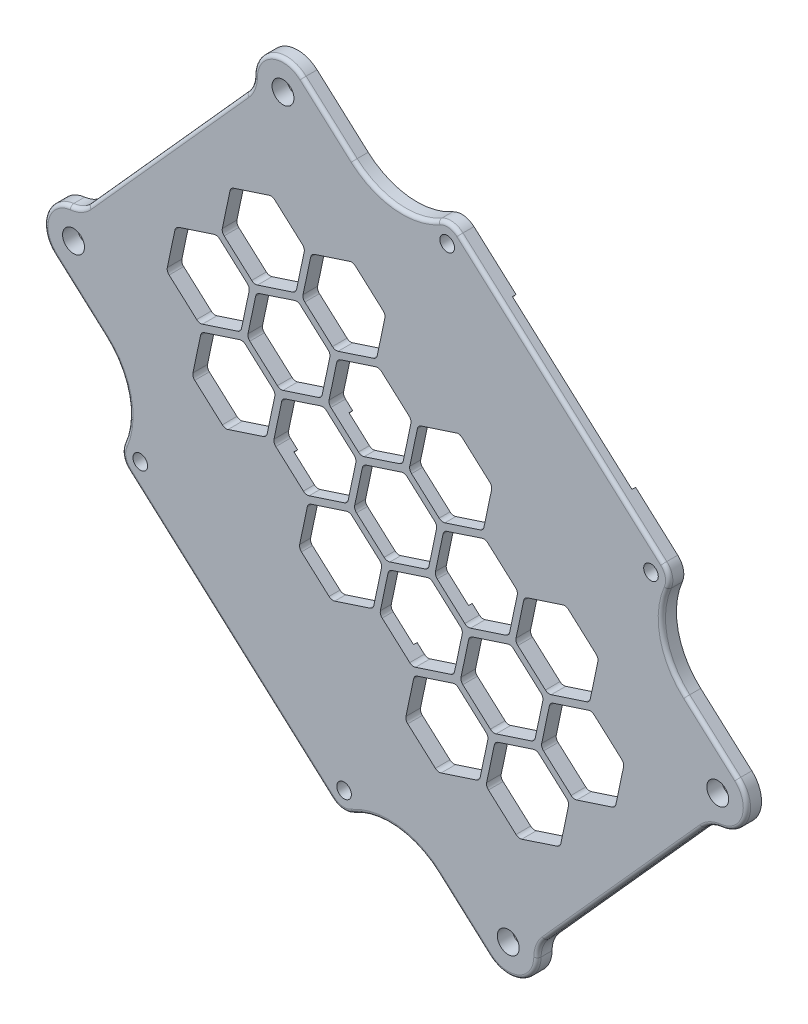
SolidWorks part; units mm, degrees
ref_plane "前视基准面" through (0, 0, 0) normal (0, 0, 1) x (1, 0, 0)
ref_plane "上视基准面" through (0, 0, 0) normal (0, 1, 0) x (1, 0, 0)
ref_plane "右视基准面" through (0, 0, 0) normal (1, 0, 0) x (0, 0, -1)
sketch "草图1" plane through (0, 0, 0) normal (0, 0, 1) x (1, 0, 0)
  line L0 (80, 0.003) -> (139.5685, -53.3973) construction
  line L1 (82.67, 2.9814) -> (142.2386, -50.4188) construction
  line L3 (142.547, -56.0673) -> (113.8443, -88.0854) construction
  line L4 (48.6273, -34.9935) -> (108.1959, -88.3938) construction
  line L5 (79.6916, 5.6514) -> (111.1743, -91.0638) construction
  line L6 (145.217, -53.0889) -> (45.6489, -32.3235) construction
  line L7 (102.4979, -6.7354) -> (130.4207, -31.7668) construction
  line L8 (102.4979, -6.7354) -> (60.4452, -53.6456) construction
  line L9 (130.4207, -31.7668) -> (88.368, -78.677) construction
  line L10 (60.4452, -53.6456) -> (88.368, -78.677) construction
  line L11 (102.4979, -6.7354) -> (88.368, -78.677) construction
  line L12 (130.4207, -31.7668) -> (60.4452, -53.6456) construction
  line L13 (97.7059, -44.7438) -> (73.5507, -23.0898) construction
  line L14 (104.1667, -4.8739) -> (132.0894, -29.9052)
  line L15 (99.4225, -38.2558) -> (108.6518, -27.9604) construction
  line L16 (135.2338, -44.1395) -> (142.2386, -50.4188)
  line L17 (82.67, 2.9814) -> (89.6747, -3.298)
  line L18 (101.1912, -82.1144) -> (108.1959, -88.3938)
  line L19 (58.7765, -55.5071) -> (86.6992, -80.5385)
  line L20 (48.6273, -34.9935) -> (55.6321, -41.2729)
  line L21 (74.9787, -2.6021) -> (53.3402, -26.74)
  line L22 (137.5257, -58.6724) -> (115.8872, -82.8103)
  circle A0 centre (139.5685, -53.3973) radius 1.5 construction
  circle A1 centre (110.8659, -85.4154) radius 1.5 construction
  circle A2 centre (51.2974, -32.0151) radius 1.5 construction
  circle A4 centre (139.5685, -53.3973) radius 1.5
  circle A5 centre (110.8659, -85.4154) radius 1.5
  circle A6 centre (51.2974, -32.0151) radius 1.5
  circle A7 centre (80, 0.003) radius 1.5
  arc A8 (48.3189, -29.3451) -> (48.6273, -34.9935) centre (51.2974, -32.0151) ccw construction
  arc A9 (77.0216, 2.673) -> (82.67, 2.9814) centre (80, 0.003) cw construction
  arc A10 (142.2386, -50.4188) -> (142.547, -56.0673) centre (139.5685, -53.3973) cw construction
  arc A11 (113.8443, -88.0854) -> (108.1959, -88.3938) centre (110.8659, -85.4154) cw construction
  circle A12 centre (102.4979, -6.7354) radius 1
  circle A13 centre (130.4207, -31.7668) radius 1
  circle A14 centre (88.368, -78.677) radius 1
  circle A15 centre (60.4452, -53.6456) radius 1
  circle A16 centre (102.4979, -6.7354) radius 2.5 construction
  circle A17 centre (130.4207, -31.7668) radius 2.5 construction
  circle A18 centre (60.4452, -53.6456) radius 2.5 construction
  circle A19 centre (88.368, -78.677) radius 2.5 construction
  arc A20 (101.2683, -4.5587) -> (89.6747, -3.298) centre (96.3498, 4.1481) cw
  arc A21 (101.2683, -4.5587) -> (104.1667, -4.8739) centre (102.4979, -6.7354) cw
  arc A22 (132.0894, -29.9052) -> (132.7183, -32.7521) centre (130.4207, -31.7668) cw
  arc A23 (132.7183, -32.7521) -> (135.2338, -44.1395) centre (141.9089, -36.6934) ccw
  arc A24 (82.67, 2.9814) -> (77.0216, 2.673) centre (80, 0.003) ccw
  arc A25 (48.3189, -29.3451) -> (48.6273, -34.9935) centre (51.2974, -32.0151) ccw
  arc A26 (113.8443, -88.0854) -> (108.1959, -88.3938) centre (110.8659, -85.4154) cw
  arc A27 (142.2386, -50.4188) -> (142.547, -56.0673) centre (139.5685, -53.3973) cw
  arc A28 (89.5976, -80.8537) -> (101.1912, -82.1144) centre (94.5161, -89.5605) cw
  arc A29 (86.6992, -80.5385) -> (89.5976, -80.8537) centre (88.368, -78.677) ccw
  arc A30 (58.1476, -52.6603) -> (55.6321, -41.2729) centre (48.957, -48.719) ccw
  arc A31 (58.1476, -52.6603) -> (58.7765, -55.5071) centre (60.4452, -53.6456) ccw
  arc A32 (48.3189, -29.3451) -> (50.8296, -28.0425) centre (51.2974, -32.0151) cw
  arc A33 (77.0216, 2.673) -> (76.0001, 0.0355) centre (80, 0.003) ccw
  arc A34 (50.8296, -28.0425) -> (53.3402, -26.74) centre (50.3618, -24.07) ccw
  arc A35 (76.0001, 0.0355) -> (74.9787, -2.6021) centre (72.0003, 0.0679) cw
  arc A36 (113.8443, -88.0854) -> (114.8658, -85.4478) centre (110.8659, -85.4154) ccw
  arc A37 (114.8658, -85.4478) -> (115.8872, -82.8103) centre (118.8656, -85.4803) cw
  arc A38 (140.0363, -57.3698) -> (137.5257, -58.6724) centre (140.5041, -61.3424) ccw
  arc A39 (142.547, -56.0673) -> (140.0363, -57.3698) centre (139.5685, -53.3973) cw
  point P844 (87.6362, -48.7818)
  point P856 (90.2423, -51.1181)
  dimension "D5" = 4
  dimension "D8" = 2
  dimension "D9" = 5
  dimension "D10" = 10
  dimension "D11" = 4
  dimension "D3" = 4
  dimension "D4" = 4
  dimension "D6" = 6
  dimension "D7" = 37.5
extrude "凸台-拉伸1" add sketch "草图1" along normal blind 2
sketch "草图2" plane through (0, 0, 2) normal (0, 0, 1) x (1, 0, 0)
  line L0 (64.1595, -14.671) -> (126.7064, -70.7413) construction
  line L1 (74.9787, -2.6021) -> (53.3402, -26.74) construction
  line L2 (115.8872, -82.8103) -> (137.5257, -58.6724) construction
  line L3 (118.1281, -17.3896) -> (72.7378, -68.0228) construction
  line L4 (132.0894, -29.9052) -> (104.1667, -4.8739) construction
  line L5 (58.7765, -55.5071) -> (86.6992, -80.5385) construction
  line L6 (98.5173, -52.1286) -> (95.864, -44.0231) construction
  line L7 (99.9956, -46.2592) -> (101.0402, -41.2916)
  line L8 (100.7913, -40.5313) -> (97.0115, -37.1429)
  line L9 (96.2286, -36.9783) -> (91.4043, -38.5575)
  line L10 (90.8703, -39.1532) -> (89.8257, -44.1208)
  line L11 (90.0746, -44.8811) -> (93.8544, -48.2695)
  line L12 (94.6373, -48.4341) -> (99.4616, -46.8549)
  line L13 (99.744, -47.7175) -> (94.9197, -49.2967)
  line L14 (94.3857, -49.8924) -> (93.3411, -54.86)
  line L15 (93.59, -55.6203) -> (97.3698, -59.0087)
  line L16 (98.1527, -59.1734) -> (102.977, -57.5942)
  line L17 (103.511, -56.9985) -> (104.5556, -52.0309)
  line L18 (104.3067, -51.2706) -> (100.5269, -47.8822)
  line L19 (105.5662, -46.0632) -> (99.8733, -52.4137) construction
  line L20 (101.1328, -47.2063) -> (104.9126, -50.5947)
  line L21 (105.6955, -50.7593) -> (110.5198, -49.1801)
  line L22 (111.0538, -48.5844) -> (112.0984, -43.6168)
  line L23 (111.8495, -42.8565) -> (108.0697, -39.4681)
  line L24 (107.2868, -39.3035) -> (102.4624, -40.8827)
  line L25 (101.9284, -41.4784) -> (100.8839, -46.446)
  line L26 (105.1351, -44.7463) -> (96.7889, -42.9913) construction
  line L27 (116.7457, -53.135) -> (121.5701, -51.5558)
  line L28 (102.1801, -40.02) -> (107.0044, -38.4408)
  line L29 (107.5384, -37.8451) -> (108.583, -32.8775)
  line L30 (108.3341, -32.1172) -> (104.5543, -28.7288)
  line L31 (103.7714, -28.5642) -> (98.9471, -30.1434)
  line L32 (98.4131, -30.7391) -> (97.3685, -35.7067)
  line L33 (97.6174, -36.467) -> (101.3972, -39.8554)
  line L34 (93.2485, -48.9454) -> (89.4687, -45.5569)
  line L35 (88.6858, -45.3923) -> (83.8615, -46.9715)
  line L36 (83.3275, -47.5672) -> (82.2829, -52.5348)
  line L37 (82.5318, -53.2951) -> (86.3116, -56.6835)
  line L38 (87.0945, -56.8481) -> (91.9188, -55.2689)
  line L39 (92.4528, -54.6733) -> (93.4974, -49.7057)
  line L40 (122.1041, -50.9601) -> (123.1486, -45.9925)
  line L41 (122.8997, -45.2322) -> (119.1199, -41.8438)
  line L42 (118.337, -41.6792) -> (113.5127, -43.2584)
  line L43 (112.9787, -43.8541) -> (111.9341, -48.8217)
  line L44 (112.183, -49.582) -> (115.9628, -52.9704)
  line L45 (115.6984, -60.3212) -> (119.4782, -63.7097)
  line L46 (120.2611, -63.8743) -> (125.0854, -62.2951)
  line L47 (125.6194, -61.6994) -> (126.664, -56.7318)
  line L48 (126.4151, -55.9715) -> (122.6353, -52.5831)
  line L49 (121.8524, -52.4184) -> (117.0281, -53.9977)
  line L50 (116.4941, -54.5933) -> (115.4495, -59.5609)
  line L51 (114.3096, -60.8325) -> (109.4853, -62.4117)
  line L52 (108.9513, -63.0074) -> (107.9067, -67.975)
  line L53 (108.1556, -68.7353) -> (111.9354, -72.1237)
  line L54 (112.7183, -72.2883) -> (117.5427, -70.7091)
  line L55 (118.0767, -70.1134) -> (119.1212, -65.1458)
  line L56 (118.8723, -64.3855) -> (115.0925, -60.9971)
  line L57 (114.5613, -59.3742) -> (115.6058, -54.4066)
  line L58 (115.3569, -53.6463) -> (111.5771, -50.2578)
  line L59 (110.7943, -50.0932) -> (105.9699, -51.6724)
  line L60 (105.4359, -52.2681) -> (104.3914, -57.2357)
  line L61 (104.6402, -57.996) -> (108.42, -61.3844)
  line L62 (109.2029, -61.5491) -> (114.0273, -59.9699)
  line L63 (107.8141, -62.0603) -> (104.0343, -58.6719)
  line L64 (103.2515, -58.5073) -> (98.4271, -60.0865)
  line L65 (97.8931, -60.6822) -> (96.8486, -65.6498)
  line L66 (97.0974, -66.4101) -> (100.8772, -69.7985)
  line L67 (101.6601, -69.9631) -> (106.4845, -68.3839)
  line L68 (107.0185, -67.7882) -> (108.063, -62.8206)
  line L69 (95.9462, -36.1156) -> (91.1219, -37.6948)
  line L70 (97.5248, -30.5523) -> (96.4802, -35.5199)
  line L71 (93.4961, -26.4036) -> (97.2759, -29.792)
  line L72 (87.8889, -27.8182) -> (92.7132, -26.239)
  line L73 (86.3103, -33.3815) -> (87.3549, -28.4139)
  line L74 (90.339, -37.5302) -> (86.5592, -34.1418)
  line L75 (85.9533, -34.8177) -> (89.7331, -38.2061)
  line L76 (80.3461, -36.2323) -> (85.1704, -34.6531)
  line L77 (78.7675, -41.7955) -> (79.8121, -36.8279)
  line L78 (82.7962, -45.9443) -> (79.0164, -42.5558)
  line L79 (88.4034, -44.5297) -> (83.5791, -46.1089)
  line L80 (89.982, -38.9664) -> (88.9374, -43.934)
  line L81 (69.2386, -33.9204) -> (74.063, -32.3412)
  line L82 (67.6601, -39.4837) -> (68.7046, -34.5161)
  line L83 (71.6887, -43.6324) -> (67.9089, -40.244)
  line L84 (77.296, -42.2178) -> (72.4716, -43.797)
  line L85 (78.8745, -36.6545) -> (77.83, -41.6222)
  line L86 (74.8458, -32.5058) -> (78.6256, -35.8942)
  line L87 (86.7743, -26.8043) -> (82.9945, -23.4159)
  line L88 (92.3815, -25.3897) -> (87.5572, -26.9689)
  line L89 (93.9601, -19.8264) -> (92.9155, -24.794)
  line L90 (89.9314, -15.6777) -> (93.7112, -19.0661)
  line L91 (84.3242, -17.0923) -> (89.1485, -15.5131)
  line L92 (82.7456, -22.6556) -> (83.7902, -17.688)
  line L93 (75.2028, -31.0697) -> (76.2474, -26.102)
  line L94 (79.2315, -35.2184) -> (75.4517, -31.83)
  line L95 (84.8387, -33.8038) -> (80.0144, -35.383)
  line L96 (86.4173, -28.2405) -> (85.3728, -33.2081)
  line L97 (82.3886, -24.0918) -> (86.1684, -27.4802)
  line L98 (76.7814, -25.5064) -> (81.6057, -23.9272)
  line L99 (71.3304, -21.7666) -> (75.1102, -25.155)
  line L100 (65.7232, -23.1811) -> (70.5476, -21.6019)
  line L101 (64.1447, -28.7444) -> (65.1892, -23.7768)
  line L102 (68.1733, -32.8931) -> (64.3935, -29.5047)
  line L103 (73.7806, -31.4786) -> (68.9562, -33.0578)
  line L104 (75.3591, -25.9153) -> (74.3146, -30.8829)
  line L105 (81.3234, -23.0645) -> (76.499, -24.6437)
  line L106 (82.9019, -17.5012) -> (81.8574, -22.4688)
  line L107 (78.8732, -13.3525) -> (82.653, -16.7409)
  line L108 (73.266, -14.7671) -> (78.0903, -13.1879)
  line L109 (71.6875, -20.3304) -> (72.732, -15.3628)
  line L110 (75.7161, -24.4791) -> (71.9363, -21.0907)
  circle A0 centre (95.4329, -42.7062) radius 5.1962 construction
  circle A1 centre (98.9483, -53.4455) radius 5.1962 construction
  circle A2 centre (106.4911, -45.0314) radius 5.1962 construction
  circle A3 centre (102.9757, -34.2921) radius 5.1962 construction
  circle A4 centre (87.8902, -51.1202) radius 5.1962 construction
  arc A5 (71.6875, -20.3304) -> (71.9363, -21.0907) centre (72.4703, -20.495) ccw
  arc A6 (73.266, -14.7671) -> (72.732, -15.3628) centre (73.5149, -15.5274) ccw
  arc A7 (78.8732, -13.3525) -> (78.0903, -13.1879) centre (78.3392, -13.9482) ccw
  arc A8 (82.9019, -17.5012) -> (82.653, -16.7409) centre (82.119, -17.3366) ccw
  arc A9 (76.499, -24.6437) -> (75.7161, -24.4791) centre (76.2501, -23.8834) cw
  arc A10 (81.3234, -23.0645) -> (81.8574, -22.4688) centre (81.0745, -22.3042) ccw
  arc A11 (73.7806, -31.4786) -> (74.3146, -30.8829) centre (73.5317, -30.7183) ccw
  arc A12 (68.1733, -32.8931) -> (68.9562, -33.0578) centre (68.7073, -32.2975) ccw
  arc A13 (64.1447, -28.7444) -> (64.3935, -29.5047) centre (64.9275, -28.9091) ccw
  arc A14 (65.7232, -23.1811) -> (65.1892, -23.7768) centre (65.9721, -23.9414) ccw
  arc A15 (75.1102, -25.155) -> (75.3591, -25.9153) centre (74.5762, -25.7507) cw
  arc A16 (71.3304, -21.7666) -> (70.5476, -21.6019) centre (70.7964, -22.3622) ccw
  arc A17 (82.3886, -24.0918) -> (81.6057, -23.9272) centre (81.8546, -24.6875) ccw
  arc A18 (86.4173, -28.2405) -> (86.1684, -27.4802) centre (85.6344, -28.0759) ccw
  arc A19 (84.8387, -33.8038) -> (85.3728, -33.2081) centre (84.5899, -33.0435) ccw
  arc A20 (79.2315, -35.2184) -> (80.0144, -35.383) centre (79.7655, -34.6227) ccw
  arc A21 (76.2474, -26.102) -> (76.7814, -25.5064) centre (77.0303, -26.2667) cw
  arc A22 (75.2028, -31.0697) -> (75.4517, -31.83) centre (75.9857, -31.2343) ccw
  arc A23 (84.3242, -17.0923) -> (83.7902, -17.688) centre (84.5731, -17.8526) ccw
  arc A24 (89.9314, -15.6777) -> (89.1485, -15.5131) centre (89.3974, -16.2734) ccw
  arc A25 (93.9601, -19.8264) -> (93.7112, -19.0661) centre (93.1772, -19.6618) ccw
  arc A26 (92.3815, -25.3897) -> (92.9155, -24.794) centre (92.1327, -24.6294) ccw
  arc A27 (82.9945, -23.4159) -> (82.7456, -22.6556) centre (83.5285, -22.8202) cw
  arc A28 (86.7743, -26.8043) -> (87.5572, -26.9689) centre (87.3083, -26.2086) ccw
  arc A29 (78.8745, -36.6545) -> (78.6256, -35.8942) centre (78.0916, -36.4899) ccw
  arc A30 (77.296, -42.2178) -> (77.83, -41.6222) centre (77.0471, -41.4575) ccw
  arc A31 (71.6887, -43.6324) -> (72.4716, -43.797) centre (72.2227, -43.0367) ccw
  arc A32 (67.6601, -39.4837) -> (67.9089, -40.244) centre (68.4429, -39.6483) ccw
  arc A33 (74.063, -32.3412) -> (74.8458, -32.5058) centre (74.3118, -33.1015) cw
  arc A34 (69.2386, -33.9204) -> (68.7046, -34.5161) centre (69.4875, -34.6807) ccw
  arc A35 (88.4034, -44.5297) -> (88.9374, -43.934) centre (88.1546, -43.7694) ccw
  arc A36 (82.7962, -45.9443) -> (83.5791, -46.1089) centre (83.3302, -45.3486) ccw
  arc A37 (78.7675, -41.7955) -> (79.0164, -42.5558) centre (79.5504, -41.9602) ccw
  arc A38 (80.3461, -36.2323) -> (79.8121, -36.8279) centre (80.595, -36.9926) ccw
  arc A39 (89.7331, -38.2061) -> (89.982, -38.9664) centre (89.1991, -38.8018) cw
  arc A40 (85.9533, -34.8177) -> (85.1704, -34.6531) centre (85.4193, -35.4134) ccw
  arc A41 (86.3103, -33.3815) -> (86.5592, -34.1418) centre (87.0932, -33.5461) ccw
  arc A42 (87.8889, -27.8182) -> (87.3549, -28.4139) centre (88.1378, -28.5785) ccw
  arc A43 (93.4961, -26.4036) -> (92.7132, -26.239) centre (92.9621, -26.9993) ccw
  arc A44 (97.5248, -30.5523) -> (97.2759, -29.792) centre (96.7419, -30.3877) ccw
  arc A45 (106.4845, -68.3839) -> (107.0185, -67.7882) centre (106.2356, -67.6236) ccw
  arc A46 (100.8772, -69.7985) -> (101.6601, -69.9631) centre (101.4113, -69.2028) ccw
  arc A47 (96.8486, -65.6498) -> (97.0974, -66.4101) centre (97.6314, -65.8144) ccw
  arc A48 (98.4271, -60.0865) -> (97.8931, -60.6822) centre (98.676, -60.8468) ccw
  arc A49 (104.0343, -58.6719) -> (103.2515, -58.5073) centre (103.5003, -59.2676) ccw
  arc A50 (107.8141, -62.0603) -> (108.063, -62.8206) centre (107.2801, -62.656) cw
  arc A51 (111.9341, -48.8217) -> (112.183, -49.582) centre (112.717, -48.9863) ccw
  arc A52 (113.5127, -43.2584) -> (112.9787, -43.8541) centre (113.7616, -44.0187) ccw
  arc A53 (119.1199, -41.8438) -> (118.337, -41.6792) centre (118.5859, -42.4395) ccw
  arc A54 (123.1486, -45.9925) -> (122.8997, -45.2322) centre (122.3657, -45.8279) ccw
  arc A55 (121.5701, -51.5558) -> (122.1041, -50.9601) centre (121.3212, -50.7955) ccw
  arc A56 (116.7457, -53.135) -> (115.9628, -52.9704) centre (116.4968, -52.3747) cw
  arc A57 (117.0281, -53.9977) -> (116.4941, -54.5933) centre (117.277, -54.758) ccw
  arc A58 (122.6353, -52.5831) -> (121.8524, -52.4184) centre (122.1013, -53.1788) ccw
  arc A59 (126.664, -56.7318) -> (126.4151, -55.9715) centre (125.8811, -56.5672) ccw
  arc A60 (125.0854, -62.2951) -> (125.6194, -61.6994) centre (124.8366, -61.5348) ccw
  arc A61 (119.4782, -63.7097) -> (120.2611, -63.8743) centre (120.0122, -63.114) ccw
  arc A62 (115.6984, -60.3212) -> (115.4495, -59.5609) centre (116.2324, -59.7256) cw
  arc A63 (119.1212, -65.1458) -> (118.8723, -64.3855) centre (118.3383, -64.9812) ccw
  arc A64 (117.5427, -70.7091) -> (118.0767, -70.1134) centre (117.2938, -69.9488) ccw
  arc A65 (111.9354, -72.1237) -> (112.7183, -72.2883) centre (112.4694, -71.528) ccw
  arc A66 (107.9067, -67.975) -> (108.1556, -68.7353) centre (108.6896, -68.1396) ccw
  arc A67 (109.4853, -62.4117) -> (108.9513, -63.0074) centre (109.7342, -63.172) ccw
  arc A68 (114.3096, -60.8325) -> (115.0925, -60.9971) centre (114.5585, -61.5928) cw
  arc A69 (108.42, -61.3844) -> (109.2029, -61.5491) centre (108.954, -60.7887) ccw
  arc A70 (104.3914, -57.2357) -> (104.6402, -57.996) centre (105.1742, -57.4003) ccw
  arc A71 (105.9699, -51.6724) -> (105.4359, -52.2681) centre (106.2188, -52.4327) ccw
  arc A72 (111.5771, -50.2578) -> (110.7943, -50.0932) centre (111.0431, -50.8535) ccw
  arc A73 (115.6058, -54.4066) -> (115.3569, -53.6463) centre (114.8229, -54.2419) ccw
  arc A74 (91.1219, -37.6948) -> (90.339, -37.5302) centre (90.873, -36.9345) cw
  arc A75 (114.5613, -59.3742) -> (114.0273, -59.9699) centre (113.7784, -59.2095) cw
  arc A76 (91.9188, -55.2689) -> (92.4528, -54.6733) centre (91.67, -54.5086) ccw
  arc A77 (86.3116, -56.6835) -> (87.0945, -56.8481) centre (86.8456, -56.0878) ccw
  arc A78 (82.2829, -52.5348) -> (82.5318, -53.2951) centre (83.0658, -52.6994) ccw
  arc A79 (83.8615, -46.9715) -> (83.3275, -47.5672) centre (84.1104, -47.7318) ccw
  arc A80 (89.4687, -45.5569) -> (88.6858, -45.3923) centre (88.9347, -46.1526) ccw
  arc A81 (93.2485, -48.9454) -> (93.4974, -49.7057) centre (92.7145, -49.541) cw
  arc A82 (95.9462, -36.1156) -> (96.4802, -35.5199) centre (95.6974, -35.3553) ccw
  arc A83 (97.3685, -35.7067) -> (97.6174, -36.467) centre (98.1514, -35.8713) ccw
  arc A84 (98.9471, -30.1434) -> (98.4131, -30.7391) centre (99.1959, -30.9037) ccw
  arc A85 (104.5543, -28.7288) -> (103.7714, -28.5642) centre (104.0203, -29.3245) ccw
  arc A86 (108.583, -32.8775) -> (108.3341, -32.1172) centre (107.8001, -32.7129) ccw
  arc A87 (107.0044, -38.4408) -> (107.5384, -37.8451) centre (106.7555, -37.6805) ccw
  arc A88 (102.1801, -40.02) -> (101.3972, -39.8554) centre (101.9312, -39.2597) cw
  arc A89 (102.4624, -40.8827) -> (101.9284, -41.4784) centre (102.7113, -41.643) ccw
  arc A90 (108.0697, -39.4681) -> (107.2868, -39.3035) centre (107.5357, -40.0638) ccw
  arc A91 (112.0984, -43.6168) -> (111.8495, -42.8565) centre (111.3155, -43.4522) ccw
  arc A92 (110.5198, -49.1801) -> (111.0538, -48.5844) centre (110.2709, -48.4198) ccw
  arc A93 (104.9126, -50.5947) -> (105.6955, -50.7593) centre (105.4466, -49.999) ccw
  arc A94 (101.1328, -47.2063) -> (100.8839, -46.446) centre (101.6668, -46.6106) cw
  arc A95 (104.5556, -52.0309) -> (104.3067, -51.2706) centre (103.7727, -51.8663) ccw
  arc A96 (102.977, -57.5942) -> (103.511, -56.9985) centre (102.7281, -56.8339) ccw
  arc A97 (97.3698, -59.0087) -> (98.1527, -59.1734) centre (97.9038, -58.4131) ccw
  arc A98 (93.3411, -54.86) -> (93.59, -55.6203) centre (94.124, -55.0247) ccw
  arc A99 (94.9197, -49.2967) -> (94.3857, -49.8924) centre (95.1685, -50.057) ccw
  arc A100 (99.744, -47.7175) -> (100.5269, -47.8822) centre (99.9929, -48.4778) cw
  arc A101 (105.5662, -46.0632) -> (105.1351, -44.7463) centre (104.9705, -45.5292) ccw construction
  arc A102 (98.5173, -52.1286) -> (99.8733, -52.4137) centre (99.2776, -51.8797) ccw construction
  arc A103 (93.8544, -48.2695) -> (94.6373, -48.4341) centre (94.3884, -47.6738) ccw
  arc A104 (89.8257, -44.1208) -> (90.0746, -44.8811) centre (90.6086, -44.2854) ccw
  arc A105 (91.4043, -38.5575) -> (90.8703, -39.1532) centre (91.6531, -39.3178) ccw
  arc A106 (97.0115, -37.1429) -> (96.2286, -36.9783) centre (96.4775, -37.7386) ccw
  arc A107 (101.0402, -41.2916) -> (100.7913, -40.5313) centre (100.2573, -41.127) ccw
  arc A108 (99.9956, -46.2592) -> (99.4616, -46.8549) centre (99.2127, -46.0946) cw
  arc A109 (95.864, -44.0231) -> (96.7889, -42.9913) centre (96.6243, -43.7742) cw construction
  point P126 (71.5924, -20.7824)
  point P129 (72.827, -14.9108)
  point P132 (78.5293, -13.0442)
  point P135 (82.9969, -17.0492)
  point P138 (76.06, -24.7874)
  point P141 (81.7623, -22.9208)
  point P144 (74.2195, -31.3349)
  point P147 (68.5173, -33.2015)
  point P150 (64.0496, -29.1964)
  point P153 (65.2842, -23.3248)
  point P156 (75.4542, -25.4633)
  point P159 (70.9865, -21.4583)
  point P162 (82.0447, -23.7835)
  point P165 (86.5123, -27.7885)
  point P168 (85.2777, -33.6601)
  point P171 (79.5754, -35.5267)
  point P174 (76.3424, -25.65)
  point P177 (75.1078, -31.5216)
  point P180 (83.8852, -17.236)
  point P183 (89.5875, -15.3694)
  point P186 (94.0551, -19.3744)
  point P189 (92.8205, -25.246)
  point P192 (82.6506, -23.1076)
  point P195 (87.1182, -27.1126)
  point P198 (78.9696, -36.2025)
  point P201 (77.7349, -42.0741)
  point P204 (72.0327, -43.9407)
  point P207 (67.565, -39.9357)
  point P210 (74.5019, -32.1975)
  point P213 (68.7996, -34.0641)
  point P216 (88.8424, -44.386)
  point P219 (83.1401, -46.2526)
  point P222 (78.6725, -42.2475)
  point P225 (79.9071, -36.3759)
  point P228 (90.077, -38.5144)
  point P231 (85.6094, -34.5094)
  point P234 (86.2153, -33.8335)
  point P237 (87.4499, -27.9619)
  point P240 (93.1522, -26.0953)
  point P243 (97.6198, -30.1003)
  point P246 (106.9234, -68.2402)
  point P249 (101.2212, -70.1068)
  point P252 (96.7535, -66.1018)
  point P255 (97.9882, -60.2302)
  point P258 (103.6904, -58.3636)
  point P261 (108.1581, -62.3686)
  point P264 (111.8391, -49.2737)
  point P267 (113.0737, -43.4021)
  point P270 (118.776, -41.5355)
  point P273 (123.2436, -45.5405)
  point P276 (122.009, -51.4121)
  point P279 (116.3067, -53.2787)
  point P282 (116.5891, -54.1413)
  point P285 (122.2914, -52.2748)
  point P288 (126.759, -56.2798)
  point P291 (125.5244, -62.1514)
  point P294 (119.8221, -64.018)
  point P297 (115.3545, -60.0129)
  point P300 (119.2162, -64.6938)
  point P303 (117.9816, -70.5654)
  point P306 (112.2793, -72.432)
  point P309 (107.8117, -68.427)
  point P312 (109.0463, -62.5554)
  point P315 (114.7486, -60.6888)
  point P318 (108.764, -61.6927)
  point P321 (104.2963, -57.6877)
  point P324 (105.5309, -51.8161)
  point P327 (111.2332, -49.9495)
  point P330 (115.7009, -53.9546)
  point P333 (90.6829, -37.8385)
  point P336 (114.4662, -59.8262)
  point P351 (96.3852, -35.9719)
  point P366 (102.0235, -41.0264)
  point P369 (107.7258, -39.1598)
  point P372 (112.1934, -43.1648)
  point P375 (110.9588, -49.0364)
  point P378 (105.2565, -50.903)
  point P381 (100.7889, -46.898)
  point P384 (104.6506, -51.5789)
  point P387 (103.416, -57.4505)
  point P390 (97.7137, -59.3171)
  point P393 (93.2461, -55.312)
  point P396 (94.4807, -49.4404)
  point P399 (100.183, -47.5739)
  point P414 (96.6676, -36.8346)
  point P417 (101.1352, -40.8396)
  point P420 (99.9006, -46.7112)
  dimension "D6" = 0.8
  dimension "D1" = 6
  dimension "D2" = 11.3
  dimension "D3" = 11.3
  dimension "D4" = 11.3
  dimension "D5" = 2
extrude "切除-拉伸1" cut sketch "草图2" against normal through all both and the other way through all
sketch "草图3" plane through (0, 0, 0) normal (0, 0, -1) x (-1, 0, 0)
  line L0 (-126.3187, -24.7321) -> (-80.9285, -75.3653)
  line L1 (-126.3187, -24.7321) -> (-109.9374, -10.047)
  line L2 (-80.9285, -75.3653) -> (-64.5472, -60.6803)
  line L3 (-109.9374, -10.047) -> (-64.5472, -60.6803)
  line L4 (-126.3187, -24.7321) -> (-64.5472, -60.6803) construction
  line L5 (-80.9285, -75.3653) -> (-109.9374, -10.047) construction
  line L6 (-79.6916, 5.6514) -> (-111.1743, -91.0638) construction
  line L7 (-104.1667, -4.8739) -> (-132.0894, -29.9052) construction
  point P1 (-95.4329, -42.7062)
  point P8 (-95.4329, -42.7062)
  dimension "D1" = 22
extrude "切除-拉伸2" cut sketch "草图3" against normal blind 0.5
fillet "圆角1" radius 0.5 24 edges at (95.2687, -5.7933, 2) (102.7682, -4.25, 2) (118.1281, -17.3896, 2) (132.8618, -31.2275, 2) (132.1443, -38.8504, 2) (138.7362, -47.2792, 2) (143.3817, -54.6054, 2) (138.662, -57.7918, 2) (126.7064, -70.7413, 2) (115.1356, -84.0358, 2) (112.482, -89.0744, 2) (104.6935, -85.2541, 2) (95.5972, -79.6191, 2) (88.0977, -81.1623, 2) (72.7378, -68.0228, 2) (58.0041, -54.1849, 2) (58.7216, -46.5619, 2) (52.1297, -38.1332, 2) (47.4842, -30.807, 2) (52.2039, -27.6206, 2) (64.1595, -14.671, 2) (75.7303, -1.3766, 2) (78.3839, 3.662, 2) (86.1724, -0.1583, 2)
